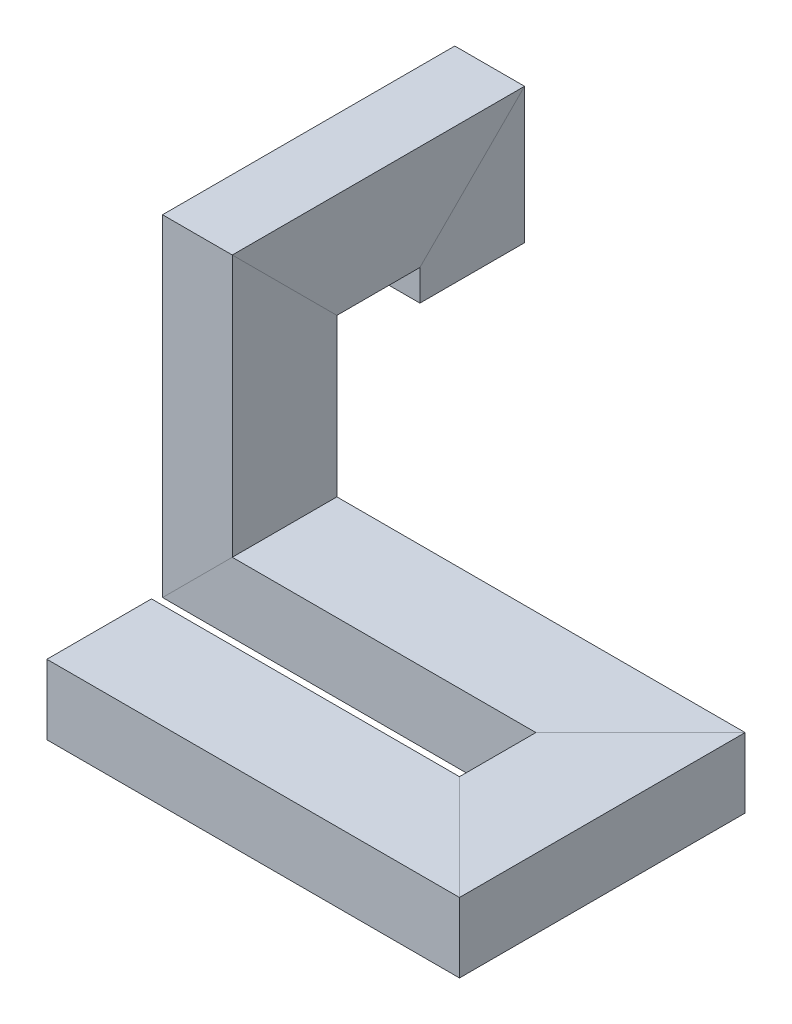
SolidWorks part; units mm, degrees
ref_plane "Front Plane" through (0, 0, 0) normal (0, 0, 1) x (1, 0, 0)
ref_plane "Top Plane" through (0, 0, 0) normal (0, 1, 0) x (1, 0, 0)
ref_plane "Right Plane" through (0, 0, 0) normal (1, 0, 0) x (0, 0, -1)
sketch3d "3DSketch1"
  line L0 (0, 0, 0) -> (59.0526, 0, 0)
  line L1 (59.0526, 0, 0) -> (59.0526, 0, -29.6688)
  line L2 (59.0526, 0, -29.6688) -> (-4.9967, 0, -29.6688)
  line L3 (-4.9967, 0, -29.6688) -> (-4.9967, 40.0456, -29.6688)
  line L4 (-4.9967, 40.0456, -29.6688) -> (-4.9967, 40.0456, -60.423)
  line L5 (-4.9967, 40.0456, -60.423) -> (-4.9967, 26.4054, -60.423)
sketch "Sketch2" plane through (0, 0, 0) normal (1, 0, 0) x (0, 0, -1)
  line L1 (8.5725, 5.715) -> (-8.5725, 5.715)
  line L2 (8.5725, 5.715) -> (8.5725, -5.715)
  line L3 (8.5725, -5.715) -> (-8.5725, -5.715)
  line L4 (-8.5725, 5.715) -> (-8.5725, -5.715)
  line L5 (8.5725, 5.715) -> (-8.5725, -5.715) construction
  line L6 (8.5725, -5.715) -> (-8.5725, 5.715) construction
  point P0 (0, 0)
  dimension "D1" = 17.145
  dimension "D2" = 11.43
sweep "Sweep1" add profiles "Sketch2" path "3DSketch1"
